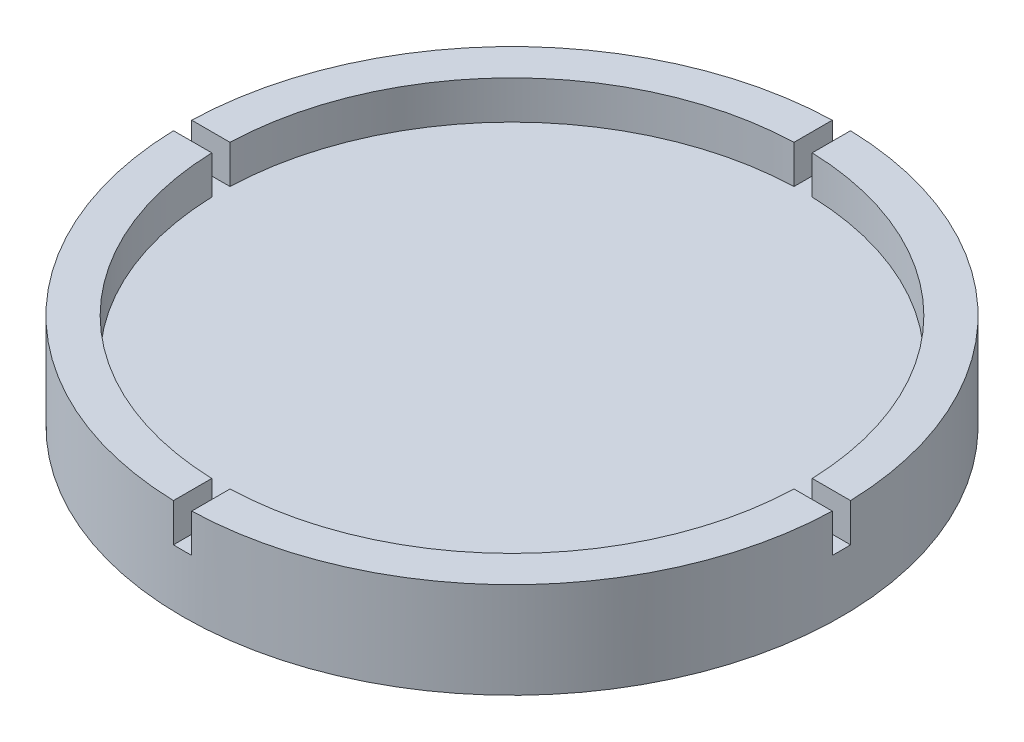
SolidWorks part; units mm, degrees
ref_plane "Front Plane" through (0, 0, 0) normal (0, 0, 1) x (1, 0, 0)
ref_plane "Top Plane" through (0, 0, 0) normal (0, 1, 0) x (1, 0, 0)
ref_plane "Right Plane" through (0, 0, 0) normal (1, 0, 0) x (0, 0, -1)
sketch "Sketch2" plane through (0, 0, 0) normal (0, 1, 0) x (1, 0, 0)
  circle A0 centre (0, 0) radius 76
extrude "Boss-Extrude1" add sketch "Sketch2" along normal blind 15
sketch "Sketch4" plane through (0, 0, 0) normal (0, -1, 0) x (-1, 0, 0)
  circle A0 centre (0, 0) radius 76
  circle A1 centre (0, 0) radius 86
extrude "Boss-Extrude2" add sketch "Sketch4" against normal blind 25
sketch "Sketch5" plane through (0, 25, 0) normal (0, 1, 0) x (1, 0, 0)
  line L2 (86, 0) -> (86, 2.38)
  line L3 (86, 2.38) -> (75.1619, 2.38)
  line L4 (75.1619, 2.38) -> (75.1619, -2.38)
  line L5 (75.1619, -2.38) -> (86.2436, -2.38)
  line L6 (86.2436, -2.38) -> (86, 0)
  line L7 (-86, 0) -> (-86, 2.38)
  line L8 (-86, 2.38) -> (-75.2221, 2.38)
  line L9 (-75.2221, 2.38) -> (-75.2221, -2.38)
  line L10 (-75.2221, -2.38) -> (-86.4571, -2.38)
  line L11 (-86.4571, -2.38) -> (-86, 0)
  line L12 (0, 86) -> (2.38, 86)
  line L13 (2.38, 86) -> (2.38, 74.1399)
  line L14 (2.38, 74.1399) -> (-2.38, 74.1399)
  line L15 (-2.38, 74.1399) -> (-2.38, 86.4471)
  line L16 (-2.38, 86.4471) -> (0, 86)
  line L17 (0, -86) -> (2.38, -86)
  line L18 (2.38, -86) -> (2.38, -74.8176)
  line L19 (2.38, -74.8176) -> (-2.38, -74.8176)
  line L20 (-2.38, -74.8176) -> (-2.38, -87.7617)
  line L21 (-2.38, -87.7617) -> (0, -86)
  circle A0 centre (0, 0) radius 86 construction
extrude "Cut-Extrude1" cut sketch "Sketch5" against normal blind 10
